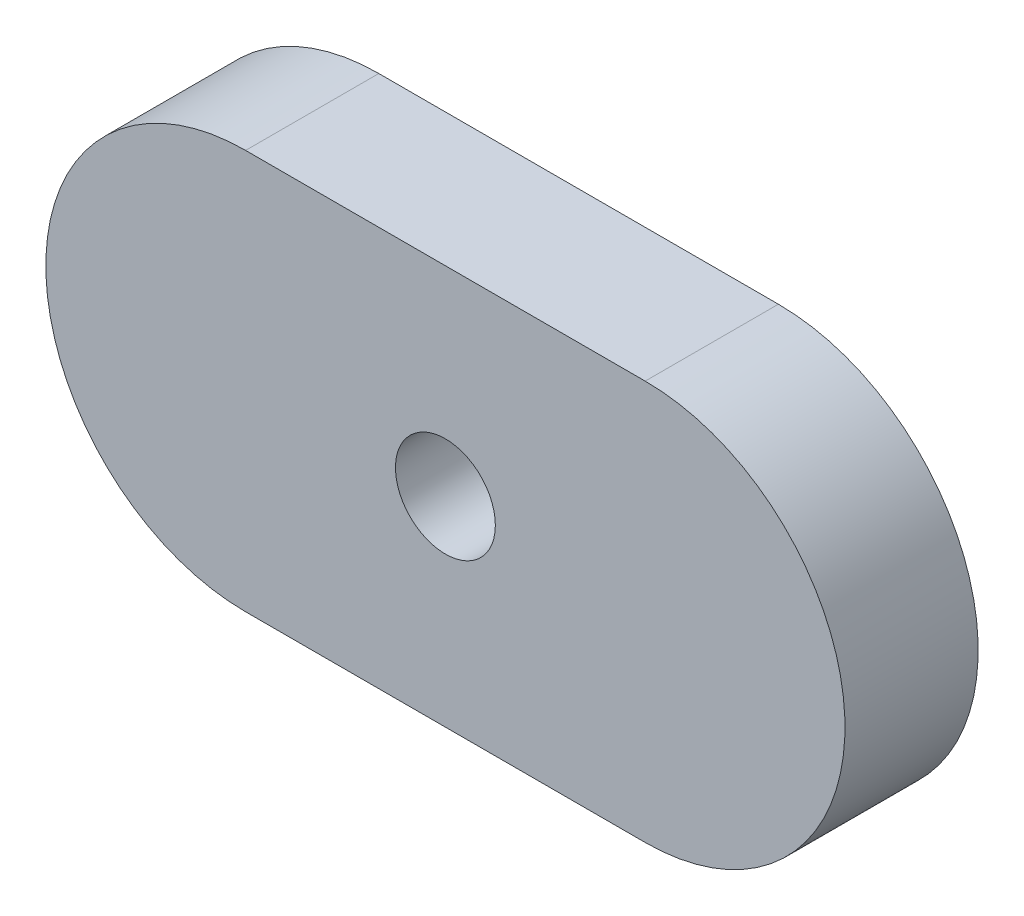
SolidWorks part; units mm, degrees
ref_plane "Front Plane" through (0, 0, 0) normal (0, 0, 1) x (1, 0, 0)
ref_plane "Top Plane" through (0, 0, 0) normal (0, 1, 0) x (1, 0, 0)
ref_plane "Right Plane" through (0, 0, 0) normal (1, 0, 0) x (0, 0, -1)
sketch "Sketch1" plane through (0, 0, 0) normal (0, 0, 1) x (1, 0, 0)
  line L0 (0, 0) -> (-1.524, 0) construction
  line L1 (0, -0.762) -> (-1.524, -0.762)
  line L2 (0, 0.762) -> (-1.524, 0.762)
  arc A0 (0, -0.762) -> (0, 0.762) centre (0, 0) ccw
  arc A1 (-1.524, 0.762) -> (-1.524, -0.762) centre (-1.524, 0) ccw
  point P3 (-0.762, 0)
  dimension "D1" = 1.524
  dimension "D2" = 0.762
extrude "Boss-Extrude1" add sketch "Sketch1" along normal blind 0.508
sketch "Sketch2" plane through (0, 0, 0.508) normal (0, 0, 1) x (1, 0, 0)
  line L0 (0, 0.762) -> (-1.524, 0.762) construction
  circle A0 centre (-0.762, 0) radius 0.1905
  point P5 (-0.762, 0.762)
  dimension "D1" = 0.762
  dimension "D3" = 0.381
  dimension "D2" = 0.762
extrude "Cut-Extrude1" cut sketch "Sketch2" against normal blind 0.508
